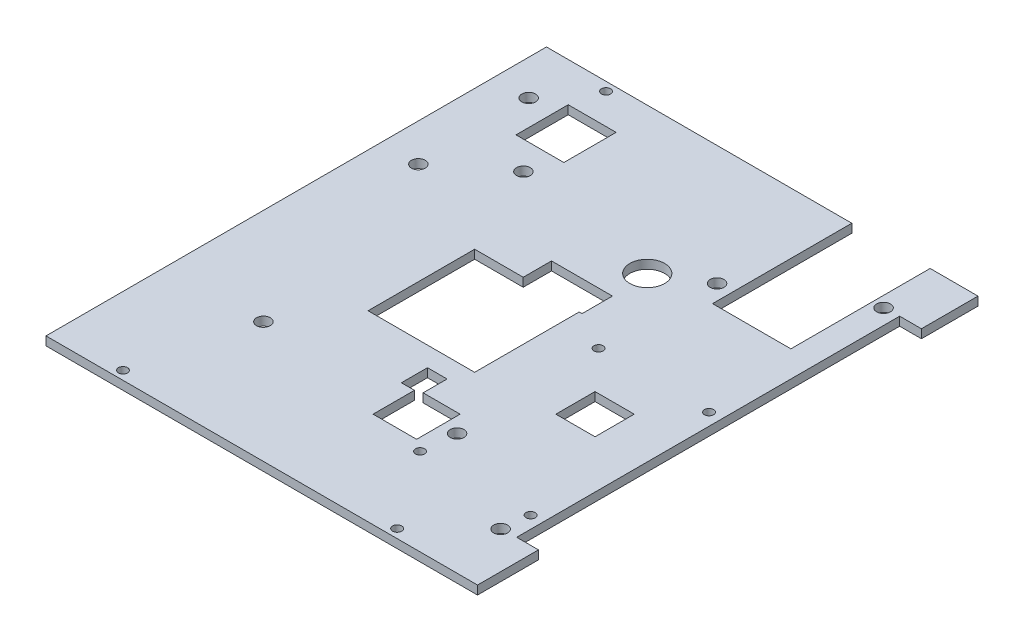
SolidWorks part; units mm, degrees
ref_plane "前视基准面" through (0, 0, 0) normal (0, 0, 1) x (1, 0, 0)
ref_plane "上视基准面" through (0, 0, 0) normal (0, 1, 0) x (1, 0, 0)
ref_plane "右视基准面" through (0, 0, 0) normal (1, 0, 0) x (0, 0, -1)
sketch "草图1" plane through (0, 0, 0) normal (0, 1, 0) x (1, 0, 0)
  line L0 (4.52, -15.78) -> (12.69, -15.78) construction
  line L1 (0, 0) -> (99.16, 0)
  line L2 (0, 0) -> (0, -115)
  line L3 (0, -115) -> (99.16, -115)
  line L4 (99.16, 0) -> (99.16, -115)
  line L5 (17.74, -23.04) -> (71.08, -23.04) construction
  line L6 (17.74, -23.04) -> (17.74, -91.62) construction
  line L7 (17.74, -91.62) -> (71.08, -91.62) construction
  line L8 (71.08, -23.04) -> (71.08, -91.62) construction
  line L9 (22.16, -27.46) -> (66.66, -27.46) construction
  line L10 (22.16, -27.46) -> (22.16, -87.2) construction
  line L11 (22.16, -87.2) -> (66.66, -87.2) construction
  line L12 (66.66, -27.46) -> (66.66, -87.2) construction
  line L13 (99.16, -8.9) -> (-0.14, -8.9) construction
  line L14 (99.16, -8.9) -> (99.16, -105.5) construction
  line L15 (99.16, -105.5) -> (-0.14, -105.5) construction
  line L16 (-0.14, -8.9) -> (-0.14, -105.5) construction
  line L17 (4.52, -8.9) -> (12.69, -8.9) construction
  line L18 (4.52, -8.9) -> (4.52, -42.03) construction
  line L19 (4.52, -42.03) -> (12.69, -42.03) construction
  line L20 (12.69, -8.9) -> (12.69, -42.03) construction
  line L21 (4.52, -34.06) -> (12.69, -34.06) construction
  line L23 (13.69, 0) -> (80.69, 0) construction
  line L24 (13.69, 0) -> (13.69, -115) construction
  line L25 (13.69, -115) -> (80.69, -115) construction
  line L26 (80.69, 0) -> (80.69, -115) construction
  line L27 (15.69, -2) -> (78.69, -2) construction
  line L28 (15.69, -2) -> (15.69, -113) construction
  line L29 (15.69, -113) -> (78.69, -113) construction
  line L30 (78.69, -2) -> (78.69, -113) construction
  line L31 (4.52, -8.9) -> (12.69, -8.9)
  line L32 (4.52, -8.9) -> (4.52, -15.78)
  line L33 (4.52, -15.78) -> (12.69, -15.78)
  line L34 (12.69, -8.9) -> (12.69, -15.78)
  line L35 (4.52, -34.06) -> (12.69, -34.06)
  line L36 (4.52, -34.06) -> (4.52, -42.03)
  line L37 (4.52, -42.03) -> (12.69, -42.03)
  line L38 (12.69, -34.06) -> (12.69, -42.03)
  line L47 (99.16, -13) -> (94.16, -13)
  line L48 (99.16, -13) -> (99.16, -101)
  line L49 (99.16, -101) -> (94.16, -101)
  line L50 (94.16, -13) -> (94.16, -101)
  line L51 (43.16, -42) -> (57.16, -42)
  line L52 (43.16, -42) -> (43.16, -49)
  line L53 (43.16, -49) -> (57.16, -49)
  line L54 (57.16, -42) -> (57.16, -49)
  line L55 (50.16, -77.5) -> (54.66, -77.5)
  line L56 (50.16, -77.5) -> (50.16, -83.5)
  line L57 (50.16, -83.5) -> (54.66, -83.5)
  line L58 (54.66, -77.5) -> (54.66, -83.5)
  line L59 (53.16, -93) -> (63.16, -93)
  line L60 (53.16, -93) -> (53.16, -83)
  line L61 (53.16, -83) -> (63.16, -83)
  line L62 (63.16, -93) -> (63.16, -83)
  line L63 (70.16, 0) -> (88.16, 0)
  line L64 (70.16, 0) -> (70.16, -32)
  line L65 (70.16, -32) -> (88.16, -32)
  line L66 (88.16, 0) -> (88.16, -32)
  line L67 (63.96, -52) -> (93.36, -52) construction
  line L68 (63.96, -52) -> (63.96, -97) construction
  line L69 (63.96, -97) -> (93.36, -97) construction
  line L70 (93.36, -52) -> (93.36, -97) construction
  line L71 (65.96, -54) -> (91.36, -54) construction
  line L72 (65.96, -54) -> (65.96, -95) construction
  line L73 (65.96, -95) -> (91.36, -95) construction
  line L74 (91.36, -54) -> (91.36, -95) construction
  line L75 (74.16, -63) -> (83.16, -63)
  line L76 (74.16, -63) -> (74.16, -72)
  line L77 (74.16, -72) -> (83.16, -72)
  line L78 (83.16, -63) -> (83.16, -72)
  line L79 (14, -9) -> (25, -9)
  line L80 (14, -9) -> (14, -21)
  line L81 (14, -21) -> (25, -21)
  line L82 (25, -9) -> (25, -21)
  line L83 (56.5, -48.5) -> (32, -48.5)
  line L84 (56.5, -48.5) -> (56.5, -73)
  line L85 (56.5, -73) -> (32, -73)
  line L86 (32, -48.5) -> (32, -73)
  circle A0 centre (22.16, -27.46) radius 1.585
  circle A1 centre (66.66, -27.46) radius 1.585
  circle A2 centre (22.16, -87.2) radius 1.585
  circle A3 centre (66.66, -87.2) radius 1.585
  circle A4 centre (90.66, -13.2) radius 1.585
  circle A5 centre (90.66, -101.2) radius 1.585
  circle A6 centre (8.12, -12.2) radius 1.585
  circle A7 centre (8.62, -38.06) radius 1.585
  circle A8 centre (15.69, -2) radius 1.05
  circle A9 centre (78.69, -2) radius 1.05
  circle A10 centre (15.69, -113) radius 1.05
  circle A11 centre (78.69, -113) radius 1.05
  circle A12 centre (56.66, -33.5) radius 4
  circle A13 centre (65.96, -54) radius 1.05
  circle A14 centre (91.36, -54) radius 1.05
  circle A15 centre (65.96, -95) radius 1.05
  circle A16 centre (91.36, -95) radius 1.05
  dimension "D11" = 3.17
  dimension "D12" = 3.17
  dimension "D13" = 3.17
  dimension "D14" = 3.17
  dimension "D19" = 3.17
  dimension "D22" = 3.17
  dimension "D30" = 3.17
  dimension "D33" = 3.17
  dimension "D42" = 2.1
  dimension "D43" = 2.1
  dimension "D44" = 2.1
  dimension "D45" = 2.1
  dimension "D55" = 8
  dimension "D74" = 2.1
  dimension "D75" = 2.1
  dimension "D76" = 2.1
  dimension "D77" = 2.1
  dimension "D2" = 115
  dimension "D3" = 53.34
  dimension "D4" = 68.58
  dimension "D5" = 4.42
  dimension "D6" = 4.42
  dimension "D7" = 4.42
  dimension "D8" = 4.42
  dimension "D9" = 99.3
  dimension "D10" = 96.6
  dimension "D15" = 68.5
  dimension "D16" = 74
  dimension "D17" = 18.3
  dimension "D18" = 22.3
  dimension "D20" = 68.5
  dimension "D21" = 14
  dimension "D23" = 94.64
  dimension "D24" = 8.17
  dimension "D25" = 6.88
  dimension "D26" = 18.28
  dimension "D27" = 7.97
  dimension "D28" = 3.6
  dimension "D29" = 3.3
  dimension "D31" = 4.1
  dimension "D32" = 4
  dimension "D34" = 9.5
  dimension "D35" = 2
  dimension "D36" = 2
  dimension "D37" = 2
  dimension "D38" = 2
  dimension "D39" = 67
  dimension "D40" = 115
  dimension "D41" = 1
  dimension "D46" = 99.16
  dimension "D47" = 13
  dimension "D48" = 5
  dimension "D49" = 88
  dimension "D50" = 11
  dimension "D51" = 18
  dimension "D52" = 32
  dimension "D53" = 33.5
  dimension "D54" = 42.5
  dimension "D56" = 42
  dimension "D57" = 7
  dimension "D58" = 42
  dimension "D59" = 14
  dimension "D60" = 77.5
  dimension "D61" = 6
  dimension "D62" = 44.5
  dimension "D63" = 4.5
  dimension "D64" = 83
  dimension "D65" = 10
  dimension "D66" = 36
  dimension "D67" = 10
  dimension "D68" = 2
  dimension "D69" = 2
  dimension "D70" = 2
  dimension "D71" = 2
  dimension "D72" = 45
  dimension "D73" = 29.4
  dimension "D78" = 18
  dimension "D79" = 2.7
  dimension "D80" = 43
  dimension "D81" = 9
  dimension "D82" = 16
  dimension "D83" = 9
  dimension "D84" = 14
  dimension "D85" = 11
  dimension "D86" = 9
  dimension "D87" = 12
  dimension "D88" = 24.5
  dimension "D89" = 42
  dimension "D90" = 32
  dimension "D91" = 24.5
extrude "凸台-拉伸1" add sketch "草图1" along normal blind 2 contours L4 L1 L2 L3 A11 A10 A9 A8 A5 A4 A3 A2 A1 A0 | L32 L33 L2 L31 A6 | L36 L37 L2 L35 A7
